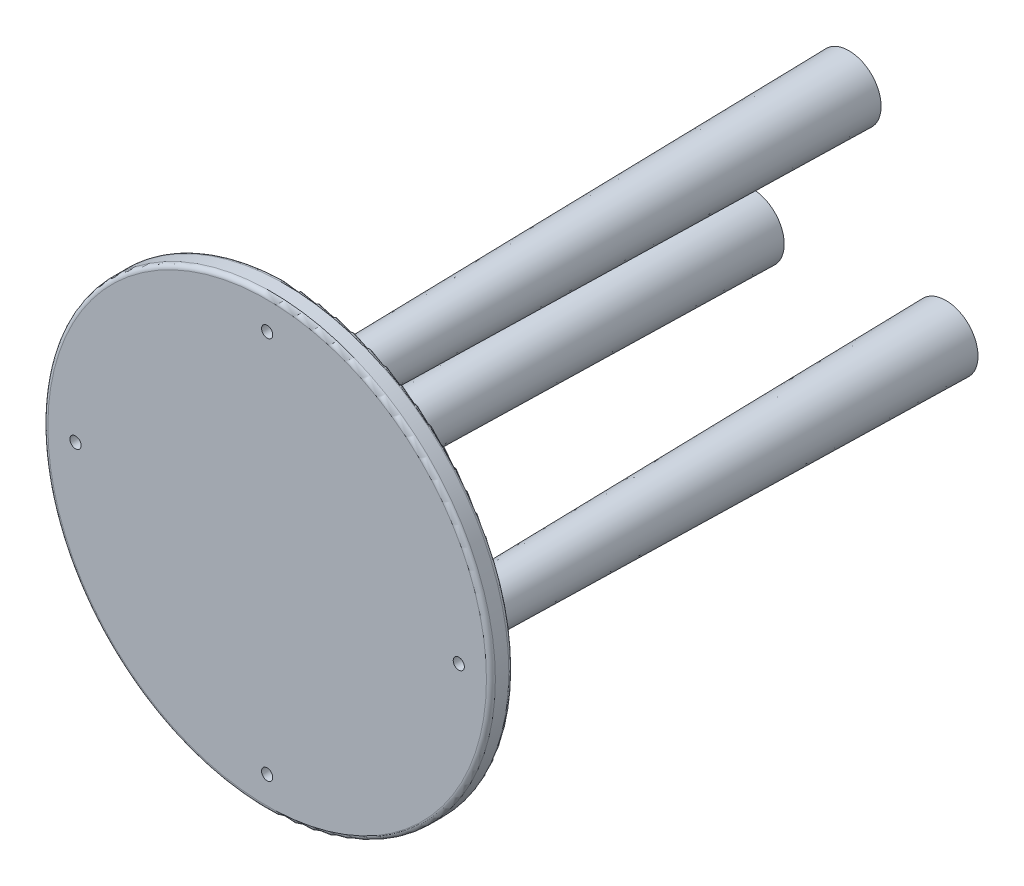
SolidWorks part; units mm, degrees
ref_plane "Front Plane" through (0, 0, 0) normal (0, 0, 1) x (1, 0, 0)
ref_plane "Top Plane" through (0, 0, 0) normal (0, 1, 0) x (1, 0, 0)
ref_plane "Right Plane" through (0, 0, 0) normal (1, 0, 0) x (0, 0, -1)
sketch "Sketch1" plane through (0, 0, 0) normal (0, 0, 1) x (1, 0, 0)
  circle A0 centre (0, 0) radius 100
  dimension "D1" = 200
extrude "Boss-Extrude1" add sketch "Sketch1" along normal blind 10
sketch "Sketch2" plane through (0, 0, 0) normal (0, 0, 1) x (1, 0, 0)
  circle A0 centre (0, 50) radius 10
  circle A1 centre (43.3013, -25) radius 10
  circle A2 centre (-43.3013, -25) radius 10
  point P9 (0, 0)
  dimension "D2" = 20
  dimension "D3" = 50
  dimension "D1" = 3
extrude "Boss-Extrude2" add sketch "Sketch2" against normal blind 250 draft 1 draft outward yes
fillet "Fillet1" radius 2 1 edges at (100, 0, 10)
fillet "Fillet2" radius 2 1 edges at (100, 0, 0)
sketch "Sketch3" plane through (0, 0, 10) normal (0, 0, 1) x (1, 0, 0)
  circle A0 centre (0, 0) radius 85.59 construction
  dimension "D1" = 171.18
sketch "Sketch4" plane through (0, 0, 10) normal (0, 0, 1) x (1, 0, 0)
  circle A0 centre (0, 85.59) radius 2.5
  circle A1 centre (0, 0) radius 85.59 construction
  dimension "D1" = 5
extrude "Cut-Extrude1" cut sketch "Sketch4" against normal up to next
fillet "Fillet3" radius 4 3 edges at (10, 50, 0) (-33.3013, -25, 0) (53.3013, -25, 0)
pattern_circular "CirPattern1" count 4 over 360 about axis through (0, -0.0557, 0) along (0, 0, 1) of "Cut-Extrude1"
